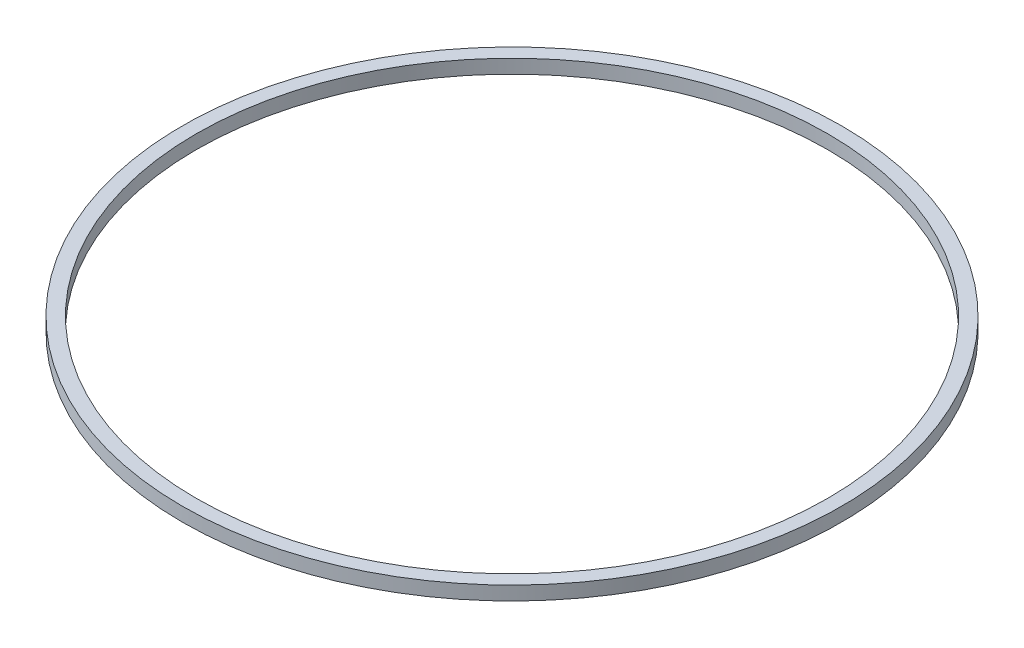
SolidWorks part; units mm, degrees
ref_plane "Front Plane" through (0, 0, 0) normal (0, 0, 1) x (1, 0, 0)
ref_plane "Top Plane" through (0, 0, 0) normal (0, 1, 0) x (1, 0, 0)
ref_plane "Right Plane" through (0, 0, 0) normal (1, 0, 0) x (0, 0, -1)
sketch "Sketch1" plane through (0, 0, 0) normal (0, 0, 1) x (1, 0, 0)
  line L0 (0, 0) -> (0, 3.2414) construction
  line L2 (-48.54, 0) -> (-50.6613, 0)
  line L3 (-50.6613, 0) -> (-50.6613, 2.1213)
  line L4 (-50.6613, 2.1213) -> (-48.54, 2.1213)
  line L5 (-48.54, 2.1213) -> (-48.54, 0)
  dimension "D1" = 48.54
  dimension "D2" = 3
  dimension "D3" = 97.08
revolve "Revolve1" add sketch "Sketch1" angle 360 about L0
